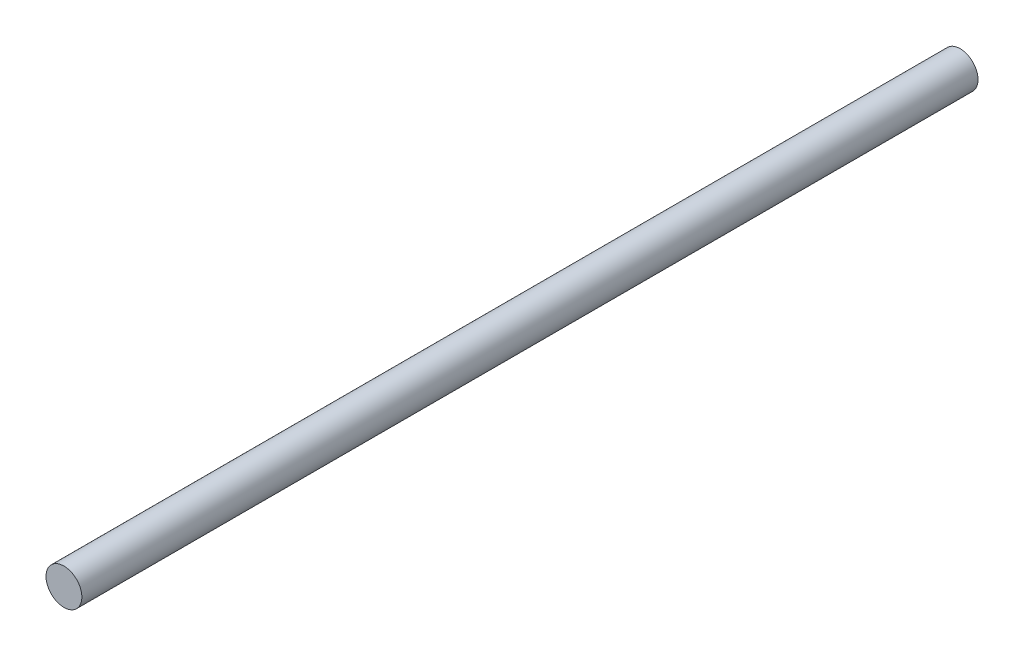
SolidWorks part; units mm, degrees
ref_plane "Front Plane" through (0, 0, 0) normal (0, 0, 1) x (1, 0, 0)
ref_plane "Top Plane" through (0, 0, 0) normal (0, 1, 0) x (1, 0, 0)
ref_plane "Right Plane" through (0, 0, 0) normal (1, 0, 0) x (0, 0, -1)
sketch "Sketch1" plane through (0, 0, 0) normal (0, 0, 1) x (1, 0, 0)
  circle A0 centre (0, 0) radius 25.4
  dimension "D1" = 50.8
extrude "Boss-Extrude1" add sketch "Sketch1" along normal blind 1270
